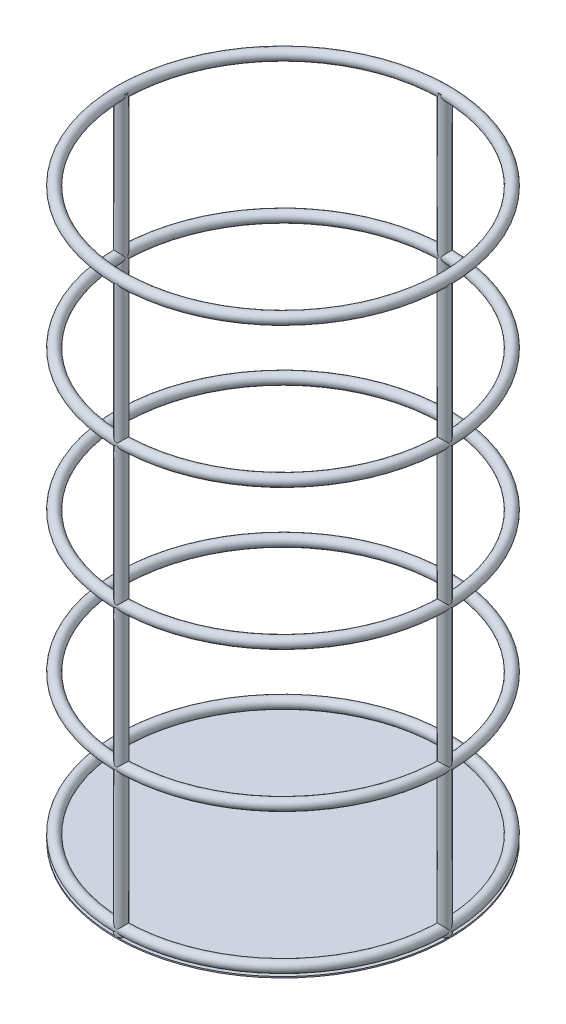
SolidWorks part; units mm, degrees
ref_plane "Front Plane" through (0, 0, 0) normal (0, 0, 1) x (1, 0, 0)
ref_plane "Top Plane" through (0, 0, 0) normal (0, 1, 0) x (1, 0, 0)
ref_plane "Right Plane" through (0, 0, 0) normal (1, 0, 0) x (0, 0, -1)
sketch "Sketch1" plane through (0, 0, 0) normal (0, 1, 0) x (1, 0, 0)
  circle A0 centre (0, 0) radius 125
  dimension "D1" = 250
extrude "Boss-Extrude1" add sketch "Sketch1" along normal blind 1
sketch "Sketch2" plane through (0, 1, 0) normal (0, 1, 0) x (1, 0, 0)
  circle A0 centre (0, 121) radius 4
  dimension "D1" = 8
  dimension "D2" = 121
extrude "Boss-Extrude2" add sketch "Sketch2" along normal blind 425
pattern_circular "CirPattern1" count 4 every 90 about axis through (0, 0, 0) along (0, 1, 0) of "Boss-Extrude2"
sketch "Sketch3" plane through (0, 0, 0) normal (0, 0, 1) x (1, 0, 0)
  line L0 (0, 13.4101) -> (0, -3.2661) construction
  line L1 (-117, 1) -> (-125, 1) construction
  circle A0 centre (-121.0963, 5) radius 4
  point P2 (0, 5.072)
  point P5 (0, 0)
  point P6 (0, 0)
  point P9 (0, -3.2661)
  point P11 (0, 13.4101)
  dimension "D2" = 8
  dimension "D1" = 121.0963
  dimension "D3" = 4
revolve "Revolve2" add sketch "Sketch3" angle 360 about L0
pattern_linear "LPattern2" count 5 spacing 105 along (0, 1, 0) of "Revolve2"
